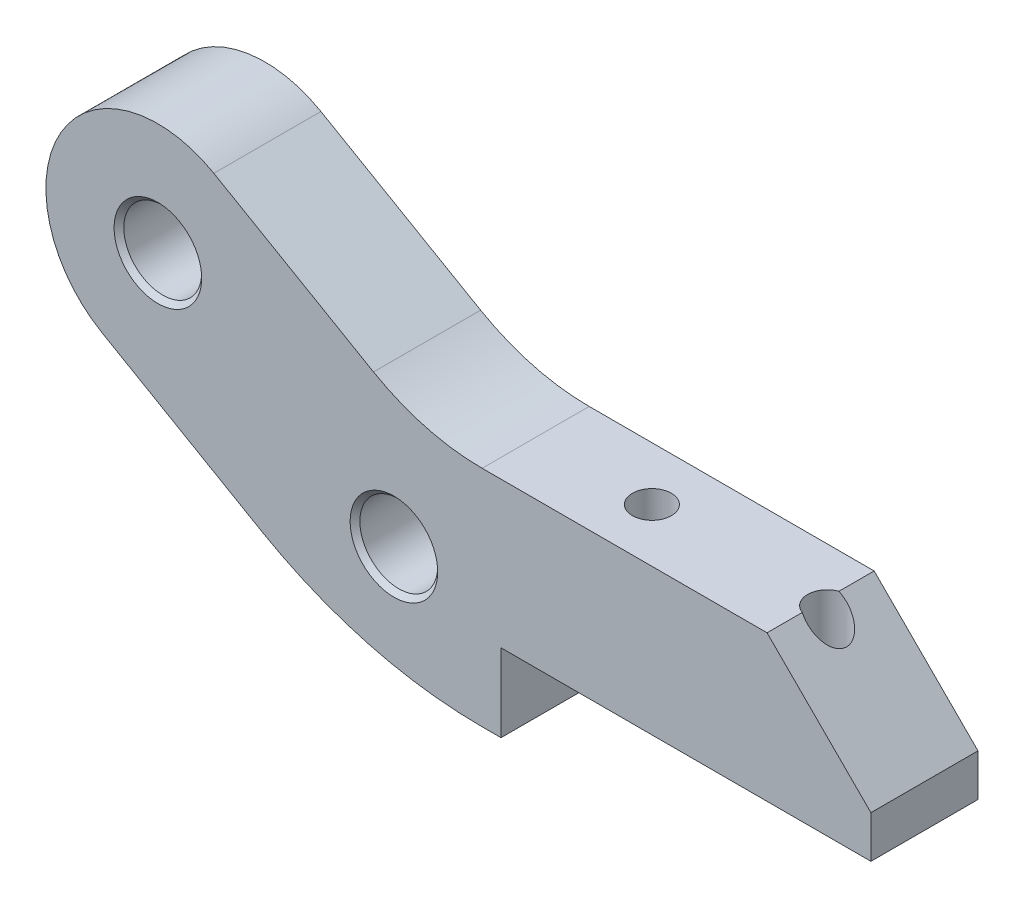
SolidWorks part; units mm, degrees
material "PW40:1:Sc:0:Re:24:"
ref_plane "Plane1" through (0, 0, 0) normal (0, 0, 1) x (1, 0, 0)
ref_plane "Plane2" through (0, 0, 0) normal (0, 1, 0) x (1, 0, 0)
ref_plane "Plane3" through (0, 0, 0) normal (1, 0, 0) x (0, 0, -1)
sketch "Esquisse1" plane through (0, 0, 0) normal (0, 0, 1) x (1, 0, 0)
  line L0 (23.0593, 31.5) -> (52.3312, 31.5)
  line L1 (11.9045, 34.4889) -> (-4.4987, 43.9593)
  line L2 (-15.9987, 24.0407) -> (0.4045, 14.5703)
  line L3 (23.0593, 8.5) -> (25, 8.5)
  line L4 (25, 8.5) -> (25, 16.5)
  line L5 (25, 16.5) -> (63, 16.5)
  line L6 (63, 16.5) -> (63, 20.8312)
  line L7 (63, 20.8312) -> (52.3312, 31.5)
  line L8 (14, 20) -> (-10.2487, 34) construction
  line L9 (14, 20) -> (65.1624, 20) construction
  arc A0 (23.0593, 31.5) -> (11.9045, 34.4889) centre (23.0593, 53.8096) cw
  arc A1 (-4.4987, 43.9593) -> (-15.9987, 24.0407) centre (-10.2487, 34) ccw
  arc A2 (0.4045, 14.5703) -> (23.0593, 8.5) centre (23.0593, 53.8096) ccw
  dimension "D1" = 23
  dimension "D2" = 23
  dimension "D3" = 8
  dimension "D4" = 30
  dimension "D5" = 28
  dimension "D6" = 11
  dimension "D7" = 49
  dimension "D8" = 225
extrude "Base-Extrusion" add sketch "Esquisse1" along normal blind 11
sketch "Esquisse2" plane through (0, 0, 11) normal (0, 0, 1) x (1, 0, 0)
  circle A0 centre (-10.2487, 34) radius 4
  dimension "D1" = 8
extrude "Enlèv. mat.-Extru.1" cut sketch "Esquisse2" against normal through all
chamfer "Chanfrein1" distance 0.5 angle 45 2 edges at (-6.2487, 34, 0) (-6.2487, 34, 11)
sketch "Esquisse3" plane through (23.4833, -13.4315, 11) normal (0, 0, 1) x (1, 0, 0)
  line L0 (-9.4833, 33.4315) -> (-33.732, 47.4315) construction
  line L2 (-39.482, 37.4723) -> (-23.0789, 28.0019) construction
  circle A0 centre (-9.4833, 33.4315) radius 4
  circle A1 centre (-33.732, 47.4315) radius 4.5 construction
  dimension "D1" = 8
  dimension "D2" = 28
extrude "Enlèv. mat.-Extru.3" cut sketch "Esquisse3" against normal through all
chamfer "Chanfrein2" distance 0.5 angle 45 2 edges at (18, 20, 0) (18, 20, 11)
sketch "Esquisse4" plane through (0, 16.5, 0) normal (0, -1, 0) x (1, 0, 0)
  line L0 (25, 11) -> (25, 0) construction
  line L1 (25, 0) -> (63, 0) construction
  circle A0 centre (35, 5.5) radius 2
  circle A1 centre (53, 5.5) radius 2
  dimension "D1" = 4
  dimension "D2" = 4
  dimension "D6" = 5.5
  dimension "D3" = 10
  dimension "D4" = 18
  dimension "D5" = 5.5
extrude "Enlèv. mat.-Extru.4" cut sketch "Esquisse4" against normal blind 21.8492
